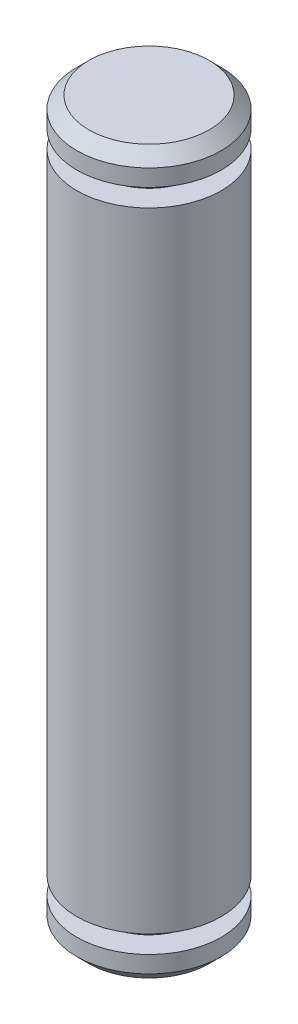
SolidWorks part; units mm, degrees
material "1.0553 (S355J0)"
ref_plane "Front Plane" through (0, 0, 0) normal (0, 0, 1) x (1, 0, 0)
ref_plane "Top Plane" through (0, 0, 0) normal (0, 1, 0) x (1, 0, 0)
ref_plane "Right Plane" through (0, 0, 0) normal (1, 0, 0) x (0, 0, -1)
sketch "Sketch1" plane through (0, 0, 0) normal (0, 1, 0) x (1, 0, 0)
  circle A0 centre (0, 0) radius 3
  dimension "D1" = 6
extrude "Boss-Extrude1" add sketch "Sketch1" along normal blind 30
sketch "Sketch2" plane through (0, 0, 0) normal (0, 0, 1) x (1, 0, 0)
  line L0 (0, -1000) -> (0, 49000) construction
  line L1 (3, 0) -> (3, 30) construction
  line L2 (3, 28.8) -> (2, 28.8)
  line L3 (3, 28.8) -> (3, 28.06)
  line L4 (3, 28.06) -> (2, 28.06)
  line L5 (2, 28.8) -> (2, 28.06)
  line L6 (3, 30) -> (-3, 30) construction
  line L7 (-3, 30) -> (-3, 0) construction
  line L8 (-1003, 15) -> (48997, 15) construction
  line L9 (2, 1.2) -> (2, 1.94)
  line L10 (3, 1.94) -> (2, 1.94)
  line L11 (3, 1.2) -> (3, 1.94)
  line L12 (3, 1.2) -> (2, 1.2)
  point P11 (-3, 15)
  dimension "D1" = 0.74
  dimension "D2" = 1.2
  dimension "D3" = 4
revolve "Cut-Revolve1" cut sketch "Sketch2" angle 360 about L0
chamfer "Chamfer1" distance 0.5 angle 45 2 edges at (0, 30, 3) (0, 0, 3)
